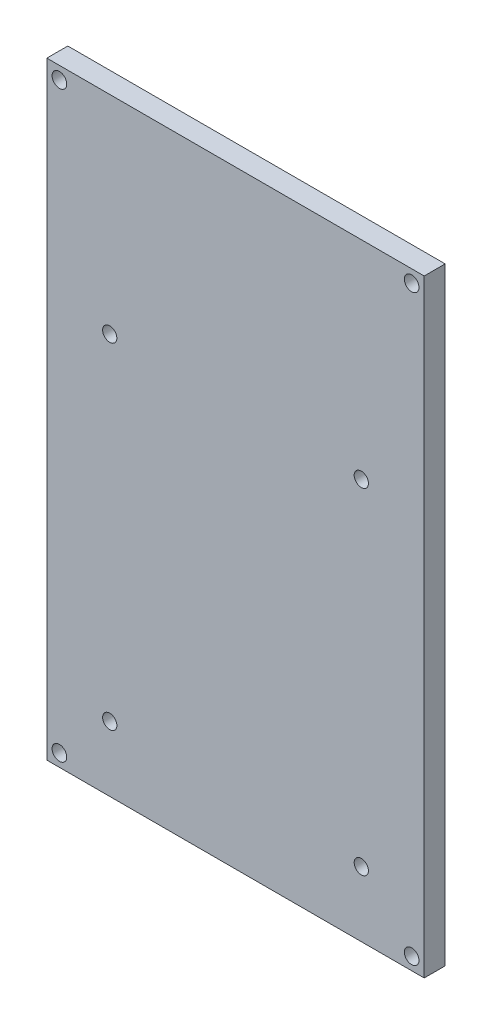
SolidWorks part; units mm, degrees
ref_plane "Front Plane" through (0, 0, 0) normal (0, 0, 1) x (1, 0, 0)
ref_plane "Top Plane" through (0, 0, 0) normal (0, 1, 0) x (1, 0, 0)
ref_plane "Right Plane" through (0, 0, 0) normal (1, 0, 0) x (0, 0, -1)
sketch "Sketch1" plane through (0, 0, 0) normal (0, 0, 1) x (1, 0, 0)
  line L1 (-45, -72.5) -> (45, -72.5)
  line L2 (-45, -72.5) -> (-45, 72.5)
  line L3 (-45, 72.5) -> (45, 72.5)
  line L4 (45, -72.5) -> (45, 72.5)
  line L5 (-45, -72.5) -> (45, 72.5) construction
  line L6 (-45, 72.5) -> (45, -72.5) construction
  point P0 (0, 0)
  dimension "D1" = 90
  dimension "D2" = 145
extrude "Boss-Extrude1" add sketch "Sketch1" along normal blind 5
sketch "Sketch2" plane through (0, 0, 0) normal (0, 0, -1) x (-1, 0, 0)
  line L0 (0, 0) -> (0, -72.5) construction
  line L1 (45, -72.5) -> (-45, -72.5) construction
  line L2 (0, 0) -> (45, 0) construction
  line L3 (45, 72.5) -> (45, -72.5) construction
  line L4 (-45, 72.5) -> (45, 72.5) construction
  line L5 (-45, -72.5) -> (-45, 72.5) construction
  circle A0 centre (-42, 69.5) radius 1.75
  circle A1 centre (-42, -69.5) radius 1.75
  circle A2 centre (42, 69.5) radius 1.75
  circle A3 centre (42, -69.5) radius 1.75
  dimension "D1" = 3
  dimension "D2" = 3
  dimension "D3" = 3.5
extrude "Cut-Extrude1" cut sketch "Sketch2" against normal through all
sketch "Sketch3" plane through (0, 0, 0) normal (0, 0, -1) x (-1, 0, 0)
  line L0 (0, 0) -> (0, -72.5) construction
  line L1 (45, -72.5) -> (-45, -72.5) construction
  line L2 (0, 0) -> (45, 0) construction
  line L3 (45, 72.5) -> (45, -72.5) construction
  line L4 (0, -17) -> (35, -17) construction
  line L5 (-35, -62) -> (35, -62) construction
  line L6 (-35, -62) -> (-35, 28) construction
  line L7 (-35, 28) -> (35, 28) construction
  line L8 (35, -62) -> (35, 28) construction
  line L9 (-35, -62) -> (35, 28) construction
  line L10 (-35, 28) -> (35, -62) construction
  circle A0 centre (-30, 23) radius 1.7
  circle A1 centre (30, 23) radius 1.7
  circle A2 centre (30, -57) radius 1.7
  circle A3 centre (-30, -57) radius 1.7
  point P5 (0, -17)
  dimension "D4" = 3.4
  dimension "D5" = 5
  dimension "D6" = 5
  dimension "D1" = 90
  dimension "D2" = 70
  dimension "D3" = 17
extrude "Cut-Extrude2" cut sketch "Sketch3" against normal through all
